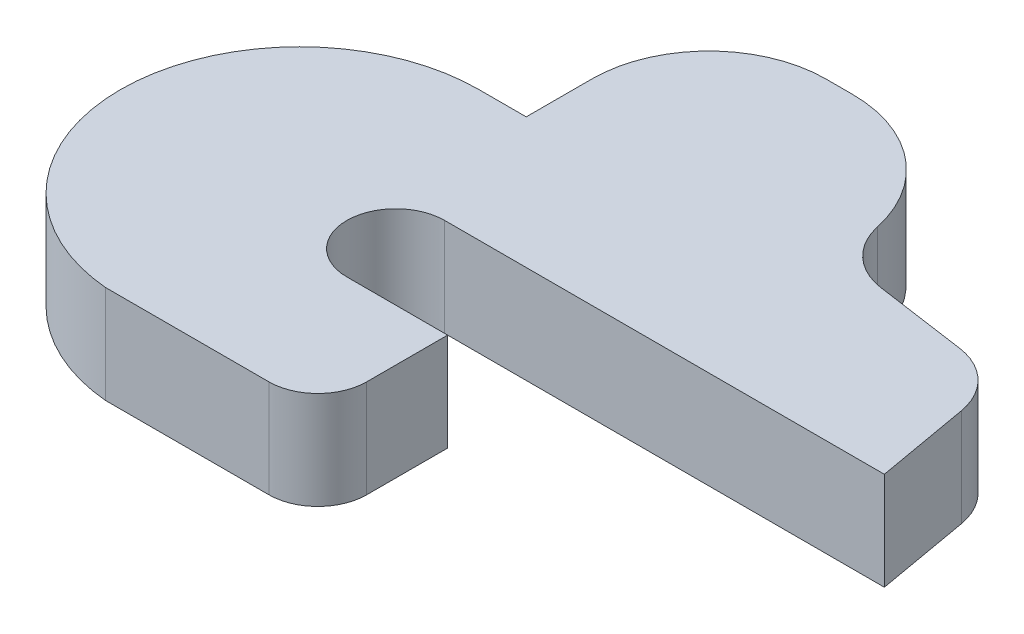
SolidWorks part; units mm, degrees
ref_plane "Front Plane" through (0, 0, 0) normal (0, 0, 1) x (1, 0, 0)
ref_plane "Top Plane" through (0, 0, 0) normal (0, 1, 0) x (1, 0, 0)
ref_plane "Right Plane" through (0, 0, 0) normal (1, 0, 0) x (0, 0, -1)
sketch "Sketch1" plane through (0, 0, 0) normal (0, 1, 0) x (1, 0, 0)
  line L0 (0, 0) -> (-3.09, 0)
  line L1 (-3.09, 3) -> (10.39, 3)
  line L2 (10.39, 3) -> (9.8844, 5.8674)
  line L5 (-0.1892, 12.6) -> (-1, 12.6)
  line L6 (-4.59, 9.01) -> (-4.59, 7)
  line L7 (-4.59, 7) -> (-6.035, 7)
  line L9 (0, -2.48) -> (0, 0)
  line L10 (-6.5036, -3.98) -> (-1.5, -3.98)
  line L11 (5.39, 7.9006) -> (8.1974, 7.5)
  arc A0 (-3.09, 0) -> (-3.09, 3) centre (-3.09, 1.5) cw
  arc A1 (9.8844, 5.8674) -> (8.1974, 7.5) centre (7.9148, 5.5201) ccw
  arc A4 (-1, 12.6) -> (-4.59, 9.01) centre (-1, 9.01) ccw
  arc A5 (-6.035, 7) -> (-6.5036, -3.98) centre (-6.035, 1.5) ccw
  arc A8 (-0.1892, 12.6) -> (3.7186, 9.4537) centre (-0.1892, 8.6) cw
  arc A9 (5.39, 7.9006) -> (3.7186, 9.4537) centre (5.6726, 9.8806) cw
  arc A10 (-1.5, -3.98) -> (0, -2.48) centre (-1.5, -2.48) ccw
  point P13 (3.7831, 8.13)
  point P43 (-11.53, 1.7345)
  point P44 (-4.59, 1.5)
  dimension "D1" = 5.6
  dimension "10.9" = 5.5
  dimension "D4" = 1.5
  dimension "4" = 4
  dimension "3" = 2
  dimension "D7" = 16.58
  dimension "D10" = 2
  dimension "D11" = 1.5
  dimension "D2" = 3.59
  dimension "D3" = 4.47
  dimension "3.65" = 4.5
  dimension "13.48" = 13.48
  dimension "80" = 80
  dimension "D8" = 6.94
  dimension "D9" = 3.09
  dimension "5" = 5
extrude "Boss-Extrude2" add sketch "Sketch1" along normal blind 3
